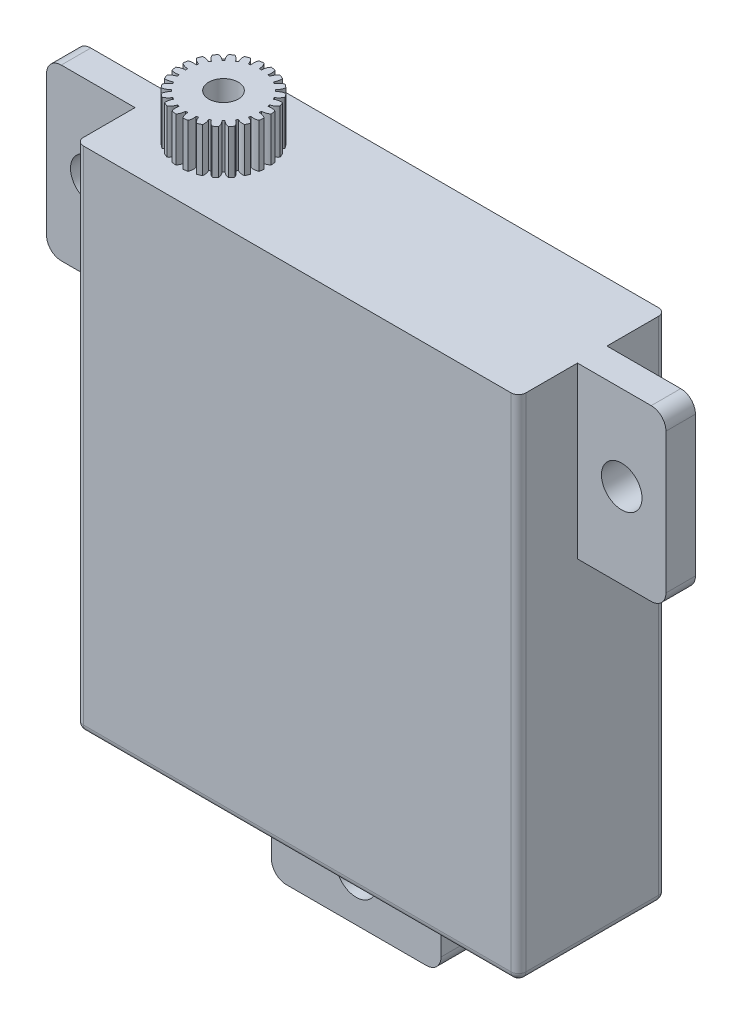
SolidWorks part; units mm, degrees
ref_plane "Front Plane" through (0, 0, 0) normal (0, 0, 1) x (1, 0, 0)
ref_plane "Top Plane" through (0, 0, 0) normal (0, 1, 0) x (1, 0, 0)
ref_plane "Right Plane" through (0, 0, 0) normal (1, 0, 0) x (0, 0, -1)
sketch "Sketch1" plane through (0, 0, 0) normal (0, 0, 1) x (1, 0, 0)
  line L1 (-14.6864, 15.7376) -> (15.3136, 15.7376)
  line L2 (-14.6864, 15.7376) -> (-14.6864, -18.7624)
  line L3 (-14.6864, -18.7624) -> (15.3136, -18.7624)
  line L4 (15.3136, 15.7376) -> (15.3136, -18.7624)
  dimension "D1" = 34.5
  dimension "D2" = 30
extrude "Boss-Extrude1" add sketch "Sketch1" along normal blind 10
ref_plane "Plane1" through (0.3136, 0, 0) normal (1, 0, 0) x (0, 0, -1)
sketch "Sketch2" plane through (0.3136, 0, 0) normal (1, 0, 0) x (0, 0, -1)
  line L0 (-10, -18.7624) -> (0, -18.7624) construction
  line L1 (-10, 15.7376) -> (0, 15.7376)
  line L2 (-10, 15.7376) -> (-10, -18.7624)
  line L3 (-10, -18.7624) -> (0, -18.7624)
  line L4 (0, 15.7376) -> (0, -18.7624)
  line L5 (0, -18.7624) -> (0, 15.7376) construction
  line L6 (-10, -18.7624) -> (-10, 15.7376) construction
  line L7 (-10, -7.2624) -> (0, -7.2624)
  line L8 (-10, 4.2376) -> (0, 4.2376)
  line L9 (-6, 15.7376) -> (-6, 4.2376)
  line L10 (-4, 15.7376) -> (-4, 4.2376)
  dimension "D1" = 34.5
  dimension "D2" = 11.5
  dimension "D3" = 11.5
  dimension "D4" = 2
  dimension "D6" = 4
sketch "Sketch3" plane through (0, -18.7624, 0) normal (0, -1, 0) x (1, 0, 0)
  line L0 (-14.6864, 0) -> (15.3136, 0) construction
  line L1 (-5.4364, 4) -> (6.0636, 4)
  line L2 (-5.4364, 4) -> (-5.4364, 6)
  line L3 (-5.4364, 6) -> (6.0636, 6)
  line L4 (6.0636, 4) -> (6.0636, 6)
  line L5 (-14.6864, 10) -> (-14.6864, 0) construction
  dimension "D1" = 11.5
  dimension "D2" = 2
  dimension "D3" = 4
  dimension "D4" = 9.25
extrude "Boss-Extrude4" add sketch "Sketch2" along normal mid plane 42 contours L10 L1 L9 L8
extrude "Boss-Extrude5" add sketch "Sketch3" along normal blind 6
fillet "Fillet2" radius 1 6 edges at (-5.4364, -24.7624, 5) (6.0636, -24.7624, 5) (21.3136, 4.2376, 5) (21.3136, 15.7376, 5) (-20.6864, 4.2376, 5) (-20.6864, 15.7376, 5)
sketch "Sketch4" plane through (0, 0, 10) normal (0, 0, 1) x (1, 0, 0)
  line L0 (-14.6864, 15.7376) -> (-19.6864, 15.7376) construction
  line L1 (-14.6864, 15.7376) -> (-14.6864, -18.7624) construction
  line L2 (6.0636, -23.7624) -> (6.0636, -18.7624) construction
  line L3 (5.0636, -24.7624) -> (-4.4364, -24.7624) construction
  line L4 (21.3136, 14.7376) -> (21.3136, 5.2376) construction
  line L5 (20.3136, 15.7376) -> (15.3136, 15.7376) construction
  circle A0 centre (-17.6864, 9.9876) radius 1.375
  circle A1 centre (18.3136, 9.9876) radius 1.375
  circle A2 centre (0.3136, -21.7624) radius 1.375
  dimension "D1" = 2.75
  dimension "D4" = 2.75
  dimension "D9" = 2.75
  dimension "D2" = 5.75
  dimension "D3" = 3
  dimension "D5" = 5.75
  dimension "D6" = 3
  dimension "D7" = 3
  dimension "D8" = 5.75
extrude "Cut-Extrude1" cut sketch "Sketch4" against normal blind 10
fillet "Fillet3" radius 0.5 8 edges at (-14.6864, -1.5124, 10) (-14.6864, -1.5124, 0) (-14.6864, -18.7624, 5) (0.3136, -18.7624, 10) (15.3136, -1.5124, 10) (15.3136, -1.5124, 0) (0.3136, -18.7624, 0) (15.3136, -18.7624, 5)
sketch "Sketch5" plane through (-14.6864, 0, 0) normal (-1, 0, 0) x (0, 0, 1)
  line L1 (3.75, -7.2624) -> (6.25, -7.2624)
  line L2 (3.75, -7.2624) -> (3.75, -13.2624)
  line L3 (3.75, -13.2624) -> (6.25, -13.2624)
  line L4 (6.25, -7.2624) -> (6.25, -13.2624)
  line L5 (9.5, -18.7624) -> (0.5, -18.7624) construction
  line L6 (5, 24.0399) -> (5, -41.6909) construction
  line L7 (10, 15.7376) -> (10, -18.2624) construction
  point P4 (5, -7.2624)
  dimension "3 mm" = 2.5
  dimension "D2" = 6
  dimension "D3" = 11.5
  dimension "D4" = 5
extrude "Cut-Extrude2" cut sketch "Sketch5" against normal blind 1
sketch "Sketch6" plane through (0, 15.7376, 0) normal (0, 1, 0) x (1, 0, 0)
  line L0 (-23.0073, -5) -> (30.4309, -5) construction
  line L2 (-20.6864, -6) -> (-20.6864, -4) construction
  line L3 (-14.6864, -4) -> (-14.6864, -0.5) construction
  circle A0 centre (-9.6864, -5) radius 3
  circle A1 centre (-9.6864, -5) radius 1
  point P7 (-20.6864, -5)
  dimension "D2" = 6
  dimension "D3" = 2
  dimension "D1" = 5
extrude "Boss-Extrude6" add sketch "Sketch6" along normal blind 3
sketch "Sketch7" plane through (0, 18.7376, 0) normal (0, 1, 0) x (1, 0, 0)
  line L0 (-9.6864, -5) -> (-9.6864, -0.9081) construction
  line L1 (-9.7614, -2.5) -> (-9.6114, -2.5)
  circle A0 centre (-9.6864, -5) radius 3
  arc A1 (-9.6114, -2.5) -> (-8.8549, -1.7167) centre (-8.8415, -2.4866) cw
  arc A2 (-9.7614, -2.5) -> (-10.5179, -1.7167) centre (-10.5313, -2.4866) ccw
  arc A3 (-9.9268, -2.0096) -> (-9.446, -2.0096) centre (-9.6864, -5) ccw
  point P9 (-9.6864, -2.5)
  circle M4 centre (-9.6864, -5) radius 3
  dimension "D2" = 0.77
  dimension "D1" = 2.5
  dimension "D3" = 0.15
extrude "Cut-Extrude3" cut sketch "Sketch7" against normal blind 3 contours L0 L1 A1 M4 | L1 L0 A0 A2
pattern_circular "CirPattern1" count 24 every 15 about axis through (-9.6864, 0, 5) along (0, 1, 0) of "Cut-Extrude3"
